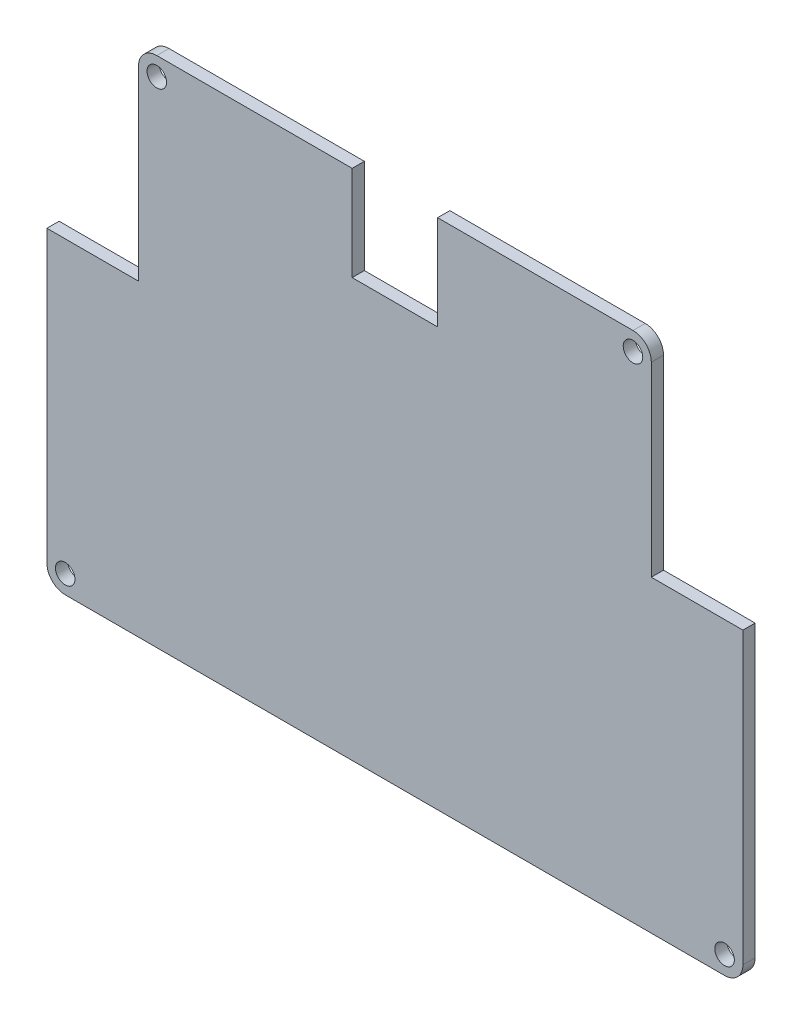
SolidWorks part; units mm, degrees
ref_plane "Front Plane" through (0, 0, 0) normal (0, 0, 1) x (1, 0, 0)
ref_plane "Top Plane" through (0, 0, 0) normal (0, 1, 0) x (1, 0, 0)
ref_plane "Right Plane" through (0, 0, 0) normal (1, 0, 0) x (0, 0, -1)
sketch "Sketch1" plane through (0, 0, 0) normal (0, 0, 1) x (1, 0, 0)
  line L0 (-42, 25.4696) -> (-57, 25.4696)
  line L1 (57, 25.4696) -> (42, 25.4696)
  line L2 (57, 25.4696) -> (57, -22.0304)
  line L3 (54, -25.0304) -> (-54, -25.0304)
  line L4 (-57, 25.4696) -> (-57, -22.0304)
  line L5 (57, 25.4696) -> (-55.3258, -24.7215) construction
  line L6 (55.3258, -24.7215) -> (-57, 25.4696) construction
  line L8 (-42, 25.4696) -> (-42, 55.9696)
  line L9 (-39, 58.9696) -> (-7, 58.9696)
  line L10 (42, 25.4696) -> (42, 55.9696)
  line L11 (-42, 25.4696) -> (40.7091, 58.4351) construction
  line L12 (-40.7091, 58.4351) -> (42, 25.4696) construction
  line L13 (7, 58.9696) -> (39, 58.9696)
  line L15 (-7, 58.9696) -> (-7, 43.4696)
  line L16 (-7, 43.4696) -> (7, 43.4696)
  line L17 (7, 58.9696) -> (7, 43.4696)
  line L18 (-7, 58.9696) -> (7, 43.4696) construction
  line L19 (-7, 43.4696) -> (7, 58.9696) construction
  line L20 (0, -1.1) -> (0, 1.1) construction
  arc A0 (57, -22.0304) -> (54, -25.0304) centre (54, -22.0304) cw
  circle A1 centre (54, -22.0304) radius 1.6
  circle A4 centre (-54, -22.0304) radius 1.6
  arc A5 (-57, -22.0304) -> (-54, -25.0304) centre (-54, -22.0304) ccw
  arc A8 (42, 55.9696) -> (39, 58.9696) centre (39, 55.9696) ccw
  circle A9 centre (39, 55.9696) radius 1.6
  arc A10 (-42, 55.9696) -> (-39, 58.9696) centre (-39, 55.9696) cw
  circle A11 centre (-39, 55.9696) radius 1.6
  point P0 (0, 0)
  point P6 (0, 42.2096)
  point P11 (0, 51.2196)
  dimension "D7" = 3
  dimension "D8" = 3.2
  dimension "D2" = 3
  dimension "D11" = 3.2
  dimension "D3" = 15
  dimension "D4" = 84
  dimension "D5" = 68.5
  dimension "D6" = 50
  dimension "D9" = 114
  dimension "D10" = 50.5
extrude "Boss-Extrude1" add sketch "Sketch1" along normal blind 2
